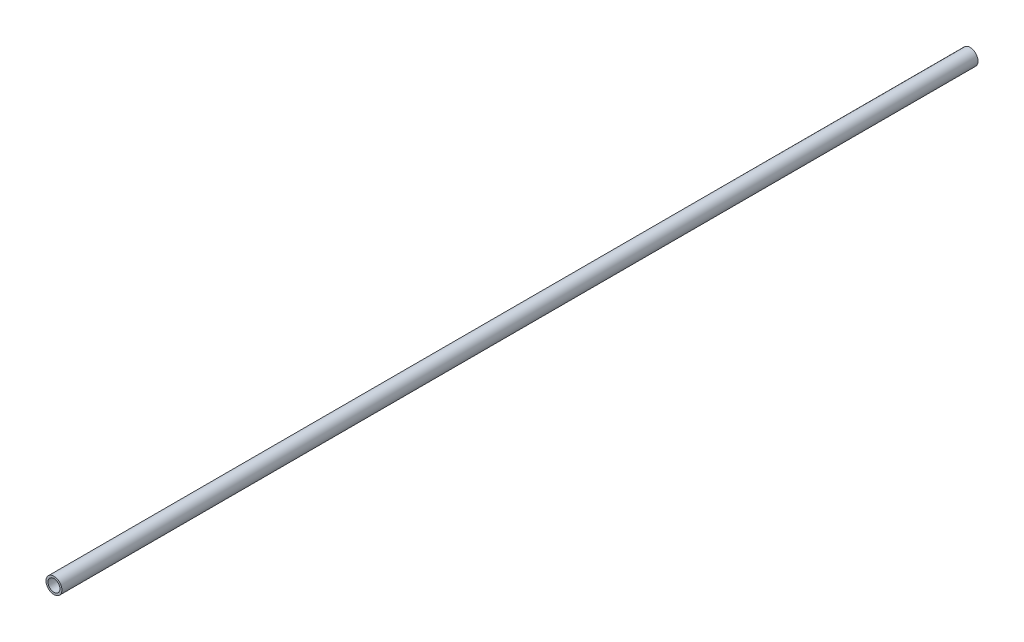
SolidWorks part; units mm, degrees
material "Hexcel AS4C (3000 丝)"
ref_plane "前视基准面" through (0, 0, 0) normal (0, 0, 1) x (1, 0, 0)
ref_plane "上视基准面" through (0, 0, 0) normal (0, 1, 0) x (1, 0, 0)
ref_plane "右视基准面" through (0, 0, 0) normal (1, 0, 0) x (0, 0, -1)
sketch "草图1" plane through (0, 0, 0) normal (0, 0, 1) x (1, 0, 0)
  line L0 (0, 18.9557) -> (0, -18.1491) construction
  line L1 (-28.6718, 0) -> (32.8516, 0) construction
  circle A0 centre (0, 0) radius 4
  circle A1 centre (0, 0) radius 3
  dimension "D1" = 6
  dimension "D2" = 8
extrude "凸台-拉伸1" add sketch "草图1" along normal blind 460
